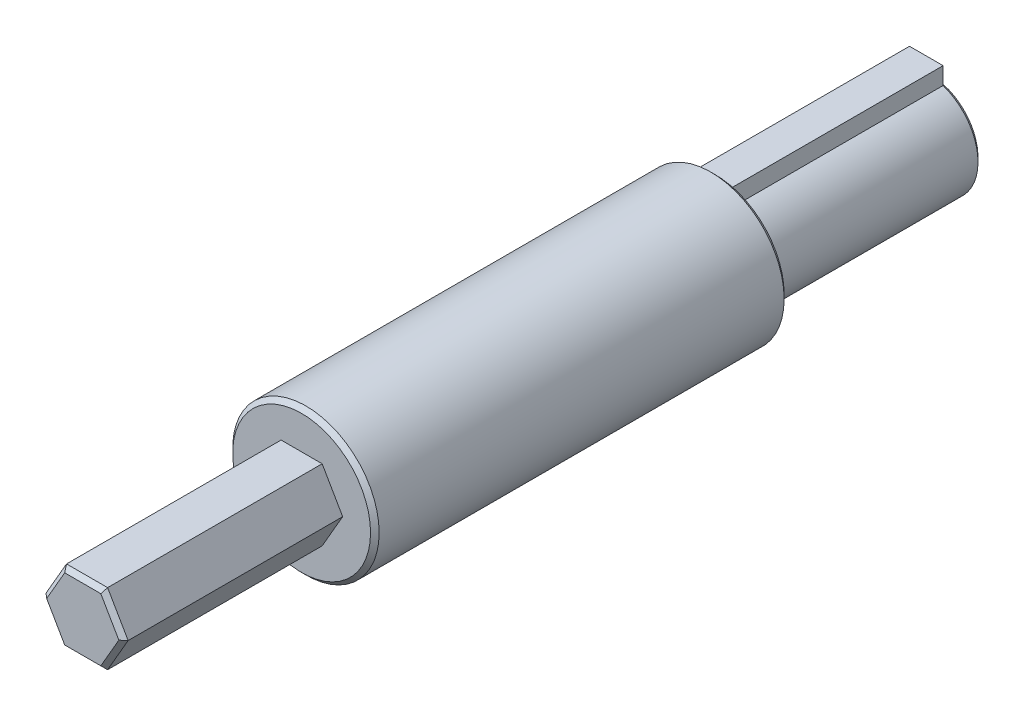
SolidWorks part; units mm, degrees
ref_plane "Front Plane" through (0, 0, 0) normal (0, 0, 1) x (1, 0, 0)
ref_plane "Top Plane" through (0, 0, 0) normal (0, 1, 0) x (1, 0, 0)
ref_plane "Right Plane" through (0, 0, 0) normal (1, 0, 0) x (0, 0, -1)
sketch "Sketch2" plane through (0, 0, 0) normal (0, 0, 1) x (1, 0, 0)
  circle A0 centre (0, 0) radius 6
  dimension "D1" = 12
extrude "Boss-Extrude1" add sketch "Sketch2" along normal blind 25.4
sketch "Sketch3" plane through (0, 0, 0) normal (0, 0, -1) x (-1, 0, 0)
  line L0 (-1.95, 5.6743) -> (-1.95, 7.6743)
  line L1 (-1.95, 7.6743) -> (1.95, 7.6743)
  line L2 (1.95, 7.6743) -> (1.95, 5.6743)
  circle A0 centre (0, 0) radius 6 construction
  arc A1 (-1.95, 5.6743) -> (1.95, 5.6743) centre (0, 0) ccw
  dimension "D1" = 3.9
  dimension "D2" = 1.95
  dimension "D3" = 2
extrude "Boss-Extrude2" add sketch "Sketch3" along normal blind 25
sketch "Sketch4" plane through (0, 0, 0) normal (0, 0, 1) x (1, 0, 0)
  circle A0 centre (0, 0) radius 8.5
  dimension "D1" = 17
extrude "Boss-Extrude3" add sketch "Sketch4" along normal blind 48
sketch "Sketch5" plane through (0, 0, 48) normal (0, 0, 1) x (1, 0, 0)
  line L1 (4.766, 0) -> (2.383, 4.1275)
  line L2 (2.383, 4.1275) -> (-2.383, 4.1275)
  line L3 (-2.383, 4.1275) -> (-4.766, 0)
  line L4 (-4.766, 0) -> (-2.383, -4.1275)
  line L5 (-2.383, -4.1275) -> (2.383, -4.1275)
  line L6 (2.383, -4.1275) -> (4.766, 0)
  circle A0 centre (0, 0) radius 4.1275 construction
  dimension "D1" = 8.255
extrude "Boss-Extrude4" add sketch "Sketch5" along normal blind 25.4
chamfer "Chamfer1" distance 0.5 angle 45 12 edges at (0, -4.1275, 73.4) (-3.5745, -2.0637, 73.4) (-3.5745, 2.0638, 73.4) (0, 4.1275, 73.4) (3.5745, 2.0638, 73.4) (3.5745, -2.0637, 73.4) (1.95, 6.6743, -25) (0, 7.6743, -25) (-1.95, 6.6743, -25) (0, -6, -25) (8.5, 0, 48) (8.5, 0, 0)
